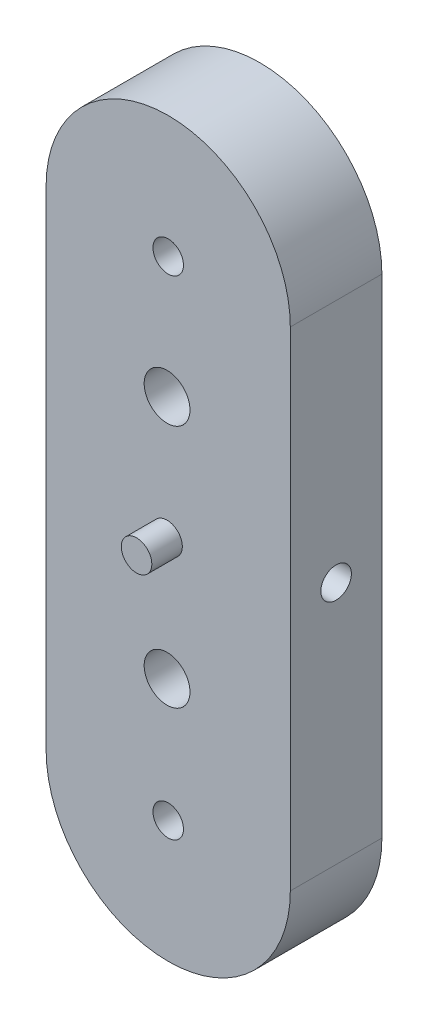
SolidWorks part; units mm, degrees
material "Pure Gold"
ref_plane "Front Plane" through (0, 0, 0) normal (0, 0, 1) x (1, 0, 0)
ref_plane "Top Plane" through (0, 0, 0) normal (0, 1, 0) x (1, 0, 0)
ref_plane "Right Plane" through (0, 0, 0) normal (1, 0, 0) x (0, 0, -1)
sketch "Sketch1" plane through (0, 0, 0) normal (0, 0, 1) x (1, 0, 0)
  line L0 (0, 0) -> (0, 203.2)
  line L1 (101.6, 203.2) -> (101.6, 0)
  arc A0 (0, 0) -> (101.6, 0) centre (50.8, 0) ccw
  arc A1 (0, 203.2) -> (101.6, 203.2) centre (50.8, 203.2) cw
  point P7 (50.8, -50.8)
  point P8 (50.8, 254)
  dimension "D1" = 203.2
  dimension "D2" = 50.8
  dimension "D3" = 50.8
extrude "Boss-Extrude1" add sketch "Sketch1" along normal blind 38.1
sketch "Sketch2" plane through (0, 0, 38.1) normal (0, 0, 1) x (1, 0, 0)
  line L0 (101.6, 0) -> (101.6, 203.2) construction
  circle A1 centre (50.8, 203.2) radius 6.35
  circle A4 centre (50.8, 0) radius 6.35
  point P5 (0, 0)
  point P6 (0, 0)
  point P9 (0, 0)
  point P14 (0, 0)
  dimension "D1" = 12.7
  dimension "D4" = 203.2
  dimension "D6" = 50.8
extrude "Cut-Extrude1" cut sketch "Sketch2" against normal through all
sketch "Sketch3" plane through (0, 0, 38.1) normal (0, 0, 1) x (1, 0, 0)
  circle A0 centre (50.3278, 152.4) radius 9.525
  circle A1 centre (50.3278, 50.8) radius 9.525
  circle A2 centre (50.8, 203.2) radius 6.35 construction
  circle A4 centre (50.8, 0) radius 6.35 construction
  point P4 (190.6462, 117.1148)
  point P5 (50.3278, 160.8965)
  dimension "D1" = 19.05
  dimension "D2" = 50.8
  dimension "D4" = 50.8
  dimension "D3" = 101.6
extrude "Cut-Extrude3" cut sketch "Sketch3" against normal offset from surface (35.56 mm away) 2.54 up to face at (57.15, 0, 0)
sketch "Sketch5" plane through (0, 0, 38.1) normal (0, 0, 1) x (1, 0, 0)
  circle A0 centre (50.3278, 101.6) radius 6.35
  circle A1 centre (50.3278, 152.4) radius 9.525 construction
  circle A2 centre (50.3278, 50.8) radius 9.525 construction
  dimension "D1" = 12.7
  dimension "D2" = 50.8
  dimension "D3" = 50.8
extrude "Boss-Extrude2" add sketch "Sketch5" along normal blind 12.7
sketch "Sketch6" plane through (101.6, 0, 0) normal (1, 0, 0) x (0, 0, -1)
  line L0 (-38.1, 0) -> (0, 0) construction
  line L7 (-38.1, 0) -> (-38.1, 203.2) construction
  line L8 (0, 0) -> (0, 203.2) construction
  circle A0 centre (-19.05, 101.6) radius 6.35
  point P2 (0, 0)
  point P5 (-38.1, 101.6)
  point P6 (-19.05, 0)
  point P9 (-13.6242, 149.0949)
  point P10 (-19.05, 203.2)
  dimension "D1" = 12.7
  dimension "D3" = 101.6
  dimension "D4" = 19.05
  dimension "D5" = 19.05
  dimension "D2" = 101.6
extrude "Cut-Extrude4" cut sketch "Sketch6" against normal through all
